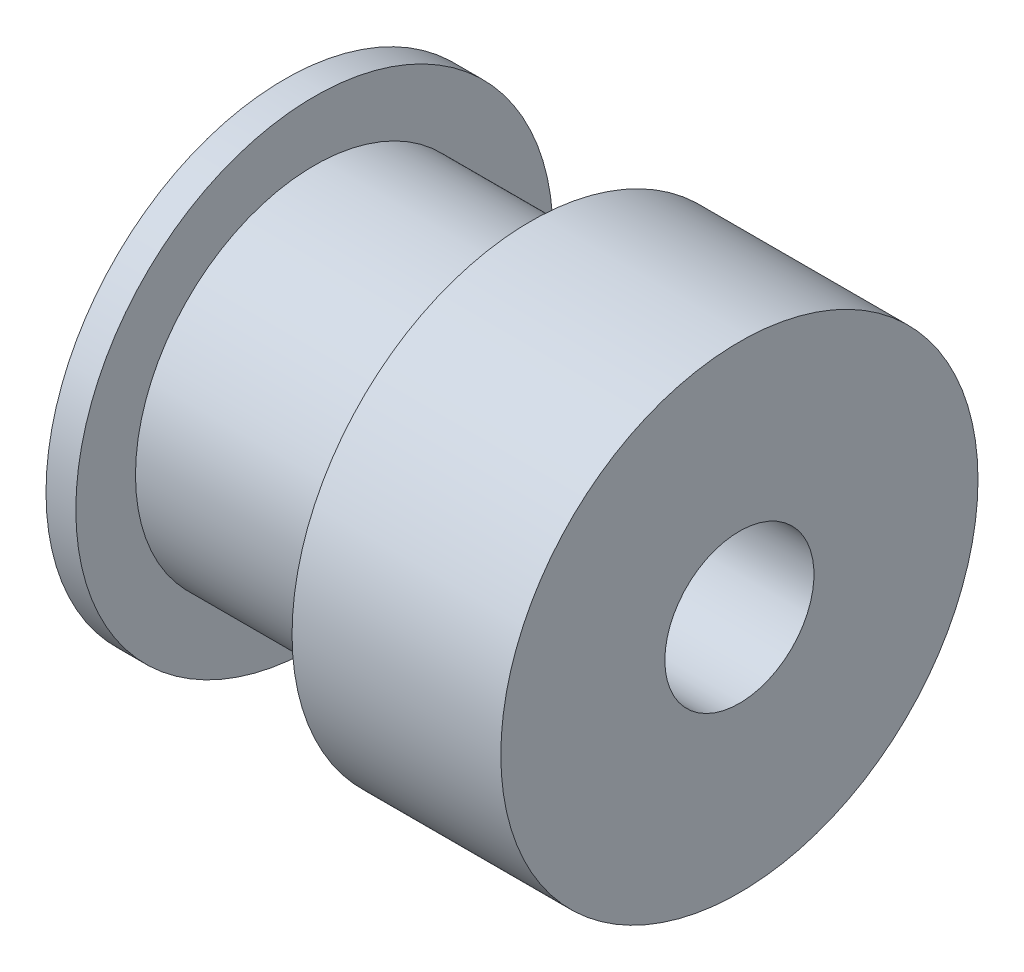
SolidWorks part; units mm, degrees
ref_plane "Front Plane" through (0, 0, 0) normal (0, 0, 1) x (1, 0, 0)
ref_plane "Top Plane" through (0, 0, 0) normal (0, 1, 0) x (1, 0, 0)
ref_plane "Right Plane" through (0, 0, 0) normal (1, 0, 0) x (0, 0, -1)
sketch "MainSketch" plane through (0, 0, 0) normal (0, 0, 1) x (1, 0, 0)
  line L0 (-7.625, 0) -> (7.625, 0) construction
  line L1 (-7.625, 8) -> (-6.625, 8)
  line L2 (-6.625, 8) -> (-6.625, 6)
  line L3 (-6.625, 6) -> (0.625, 6)
  line L4 (0.625, 6) -> (0.625, 8)
  line L5 (0.625, 8) -> (7.625, 8)
  line L6 (7.625, 8) -> (7.625, 2.5)
  line L7 (7.625, 2.5) -> (-7.625, 2.5)
  line L8 (-7.625, 2.5) -> (-7.625, 8)
  point P4 (0, 0)
  point P7 (0, 0)
  point P14 (0, 0)
  dimension "D1" = 1
  dimension "D2" = 7.25
  dimension "D3" = 7
  dimension "D4" = 8
  dimension "D5" = 2.5
  dimension "D6" = 6
revolve "Revolve1" add sketch "MainSketch" angle 360 about L0
